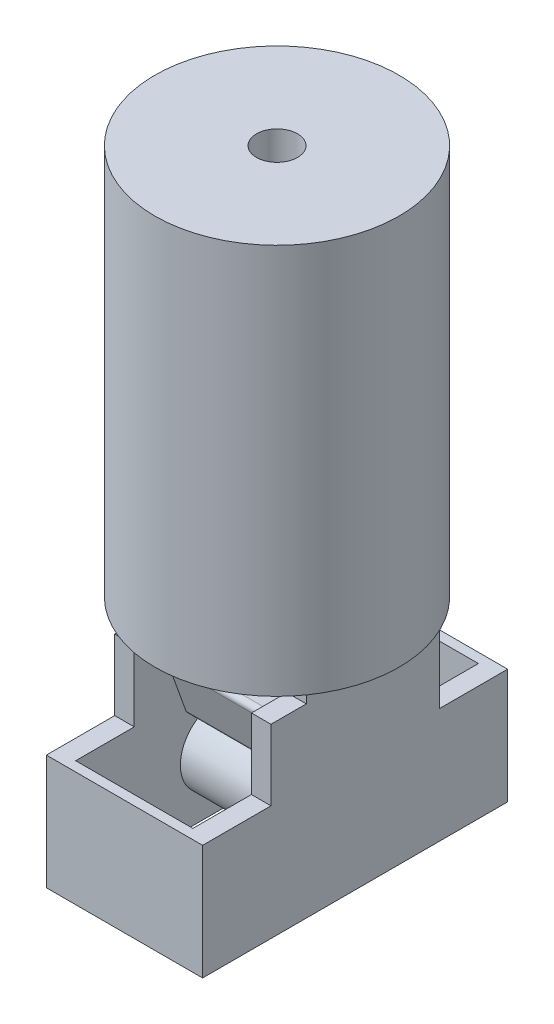
SolidWorks part; units mm, degrees
ref_plane "Front Plane" through (0, 0, 0) normal (0, 0, 1) x (1, 0, 0)
ref_plane "Top Plane" through (0, 0, 0) normal (0, 1, 0) x (1, 0, 0)
ref_plane "Right Plane" through (0, 0, 0) normal (1, 0, 0) x (0, 0, -1)
sketch "Sketch2" plane through (0, 0, 0) normal (1, 0, 0) x (0, 0, -1)
  circle A0 centre (0, 0) radius 3.9
  dimension "D1" = 7.8
extrude "Boss-Extrude1" add sketch "Sketch2" along normal blind 12
sketch "Sketch3" plane through (12, 0, 0) normal (1, 0, 0) x (0, 0, -1)
  circle A0 centre (0, 0) radius 6
  dimension "D1" = 12
extrude "Boss-Extrude2" add sketch "Sketch3" along normal blind 2
sketch "Sketch4" plane through (0, 0, 0) normal (-1, 0, 0) x (0, 0, 1)
  circle A0 centre (0, 0) radius 6
  dimension "D1" = 12
extrude "Boss-Extrude3" add sketch "Sketch4" along normal blind 2
ref_plane "Plane1" through (0, 5, 0) normal (0, 1, 0) x (1, 0, 0)
sketch "Sketch5" plane through (0, 5, 0) normal (0, 1, 0) x (1, 0, 0)
  line L1 (-3.6917, 7.3114) -> (15.8055, 7.3114)
  line L2 (-3.6917, 7.3114) -> (-3.6917, -6.5718)
  line L3 (-3.6917, -6.5718) -> (15.8055, -6.5718)
  line L4 (15.8055, 7.3114) -> (15.8055, -6.5718)
  line L5 (-3.6917, 7.3114) -> (15.8055, -6.5718) construction
  line L6 (-3.6917, -6.5718) -> (15.8055, 7.3114) construction
  point P0 (6.0569, 0.3698)
extrude "Cut-Extrude1" cut sketch "Sketch5" along normal blind 5
sketch "Sketch6" plane through (0, 5, 0) normal (0, 1, 0) x (1, 0, 0)
  line L0 (14, 3.3166) -> (12, 3.3166) construction
  line L1 (12, 3.3166) -> (12, -3.3166) construction
  line L2 (12, -3.3166) -> (14, -3.3166) construction
  line L3 (14, -3.3166) -> (14, 3.3166) construction
  line L4 (-2, -3.3166) -> (0, -3.3166) construction
  line L5 (0, -3.3166) -> (0, 3.3166) construction
  line L6 (0, 3.3166) -> (-2, 3.3166) construction
  line L7 (-2, 3.3166) -> (-2, -3.3166) construction
  line L8 (14, 3.3166) -> (12, 3.3166)
  line L9 (12, 3.3166) -> (12, -3.3166)
  line L10 (12, -3.3166) -> (14, -3.3166)
  line L11 (14, -3.3166) -> (14, 3.3166)
  line L12 (-2, -3.3166) -> (0, -3.3166)
  line L13 (0, -3.3166) -> (0, 3.3166)
  line L14 (0, 3.3166) -> (-2, 3.3166)
  line L15 (-2, 3.3166) -> (-2, -3.3166)
extrude "Boss-Extrude4" add sketch "Sketch6" along normal blind 8
sketch "Sketch7" plane through (0, 13, 0) normal (0, 1, 0) x (1, 0, 0)
  line L0 (-2, 3.3166) -> (-2, -3.3166) construction
  line L1 (-2, 5) -> (14, 5)
  line L2 (-2, 5) -> (-2, -5)
  line L3 (-2, -5) -> (14, -5)
  line L4 (14, 5) -> (14, -5)
  line L5 (-2, 5) -> (14, -5) construction
  line L6 (-2, -5) -> (14, 5) construction
  line L7 (14, -3.3166) -> (14, 3.3166) construction
  point P0 (6, 0)
  dimension "D1" = 10
  dimension "D2" = 5
extrude "Boss-Extrude5" add sketch "Sketch7" along normal blind 3
sketch "Sketch8" plane through (0, 16, 0) normal (0, 1, 0) x (1, 0, 0)
  line L0 (-2, 5) -> (-2, -5) construction
  circle A0 centre (6, 0) radius 12.5
  dimension "D1" = 25
  dimension "D2" = 8
extrude "Boss-Extrude6" add sketch "Sketch8" along normal blind 40
sketch "Sketch10" plane through (0, 56, 0) normal (0, 1, 0) x (1, 0, 0)
  circle A0 centre (6, 0) radius 2.1
  circle A1 centre (6, 0) radius 12.5 construction
  dimension "D1" = 4.2
extrude "Cut-Extrude2" cut sketch "Sketch10" against normal blind 21
sketch "Sketch11" plane through (0, 0, 3.3166) normal (0, 0, 1) x (1, 0, 0)
  line L0 (12, 13) -> (14, 13)
  line L1 (14, 13) -> (14, -6)
  line L2 (14, -6) -> (12, -6)
  line L3 (12, -6) -> (12, 13)
  line L4 (-2, 13) -> (0, 13)
  line L5 (0, 13) -> (0, -6)
  line L6 (0, -6) -> (-2, -6)
  line L7 (-2, -6) -> (-2, 13)
sketch "Sketch12" plane through (12, 0, 0) normal (-1, 0, 0) x (0, 0, 1)
  line L0 (-3.2, 4.2) -> (3.2, 4.2)
  line L1 (-5, 9.2) -> (5, 9.2) construction
  line L2 (-5, 9.2) -> (-3.2, 4.2)
  line L3 (5, 9.2) -> (3.2, 4.2)
  line L4 (-5, 9.2) -> (-5.36, 10.2)
  line L5 (-5.36, 10.2) -> (5.36, 10.2)
  line L6 (5.36, 10.2) -> (5, 9.2)
  circle A0 centre (0, 0) radius 4.2 construction
  dimension "D1" = 8.4
  dimension "D2" = 6.4
  dimension "D3" = 3.2
  dimension "D4" = 10
  dimension "D5" = 5
  dimension "D6" = 5
  dimension "D7" = 1
extrude "Boss-Extrude7" add sketch "Sketch12" along normal up to surface (12 mm away) up to face at (0, 0, -3.9)
fillet "Fillet1" radius 0.5 4 edges at (6, 4.2, -3.2) (6, 4.2, 3.2) (6, 10.2, -5.36) (6, 10.2, 5.36)
extrude "Boss-Extrude8" add sketch "Sketch11" along normal blind 11.3
sketch "Sketch13" plane through (0, 0, -3.3166) normal (0, 0, -1) x (-1, 0, 0)
  line L0 (-14, 13) -> (-12, 13)
  line L1 (-12, 13) -> (-12, -6)
  line L2 (-12, -6) -> (-14, -6)
  line L3 (-14, -6) -> (-14, 13)
  line L4 (0, 13) -> (2, 13)
  line L5 (2, 13) -> (2, -6)
  line L6 (2, -6) -> (0, -6)
  line L7 (0, -6) -> (0, 13)
extrude "Boss-Extrude9" add sketch "Sketch13" along normal blind 11.3
sketch "Sketch14" plane through (0, 0, 14.6166) normal (0, 0, 1) x (1, 0, 0)
  line L0 (-2, 13) -> (14, 13)
  line L1 (14, 13) -> (14, -6)
  line L2 (14, -6) -> (-2, -6)
  line L3 (-2, -6) -> (-2, 13)
extrude "Boss-Extrude10" add sketch "Sketch14" along normal blind 1
sketch "Sketch15" plane through (0, 0, -14.6166) normal (0, 0, -1) x (-1, 0, 0)
  line L0 (-14, 13) -> (2, 13)
  line L1 (2, 13) -> (2, -6)
  line L2 (2, -6) -> (-14, -6)
  line L3 (-14, -6) -> (-14, 13)
extrude "Boss-Extrude11" add sketch "Sketch15" along normal blind 1
sketch "Sketch16" plane through (0, 0, -15.6166) normal (0, 0, -1) x (-1, 0, 0)
  line L0 (-14, 13) -> (2, 13)
  line L1 (2, 13) -> (2, 5.7667)
  line L2 (2, -6) -> (2, 13) construction
  line L3 (2, 5.7667) -> (-14, 5.7667)
  line L4 (-14, 13) -> (-14, -6) construction
  line L5 (-14, 5.7667) -> (-14, 13)
extrude "Cut-Extrude3" cut sketch "Sketch16" against normal blind 7
sketch "Sketch17" plane through (0, 0, 15.6166) normal (0, 0, 1) x (1, 0, 0)
  line L0 (-2, 13) -> (14, 13)
  line L1 (14, 13) -> (14, 5.7667)
  line L2 (14, 5.7667) -> (-2, 5.7667)
  line L3 (-2, 5.7667) -> (-2, 13)
extrude "Cut-Extrude4" cut sketch "Sketch17" against normal blind 7
sketch "Sketch18" plane through (0, 0, 3.3166) normal (0, 0, -1) x (-1, 0, 0)
  line L4 (-12, -5) -> (-14, -5)
  line L5 (-14, -5) -> (-14, -6)
  line L6 (-14, -6) -> (-12, -6)
  line L7 (-12, -6) -> (-12, -5)
  line L8 (-12, -5) -> (-14, -5)
  line L9 (-14, -5) -> (-14, -6)
  line L10 (-14, -6) -> (-12, -6)
  line L11 (-12, -6) -> (-12, -5)
  dimension "D1" = 0
extrude "Boss-Extrude12" add sketch "Sketch18" along normal up to surface (6.6332 mm away) up to face at (13, -5.5, -3.3166)
sketch "Sketch19" plane through (0, 0, 3.3166) normal (0, 0, -1) x (-1, 0, 0)
  line L4 (2, -5) -> (0, -5)
  line L5 (0, -5) -> (0, -6)
  line L6 (0, -6) -> (2, -6)
  line L7 (2, -6) -> (2, -5)
  line L8 (2, -5) -> (0, -5)
  line L9 (0, -5) -> (0, -6)
  line L10 (0, -6) -> (2, -6)
  line L11 (2, -6) -> (2, -5)
  dimension "D1" = 0
extrude "Boss-Extrude13" add sketch "Sketch19" along normal up to surface (6.6332 mm away) up to face at (-1, -5.5, -3.3166)
equation "\"D3@Sketch12\"=\"D2@Sketch12\"/2"
equation "\"D6@Sketch12\"=\"D4@Sketch12\"/2"
